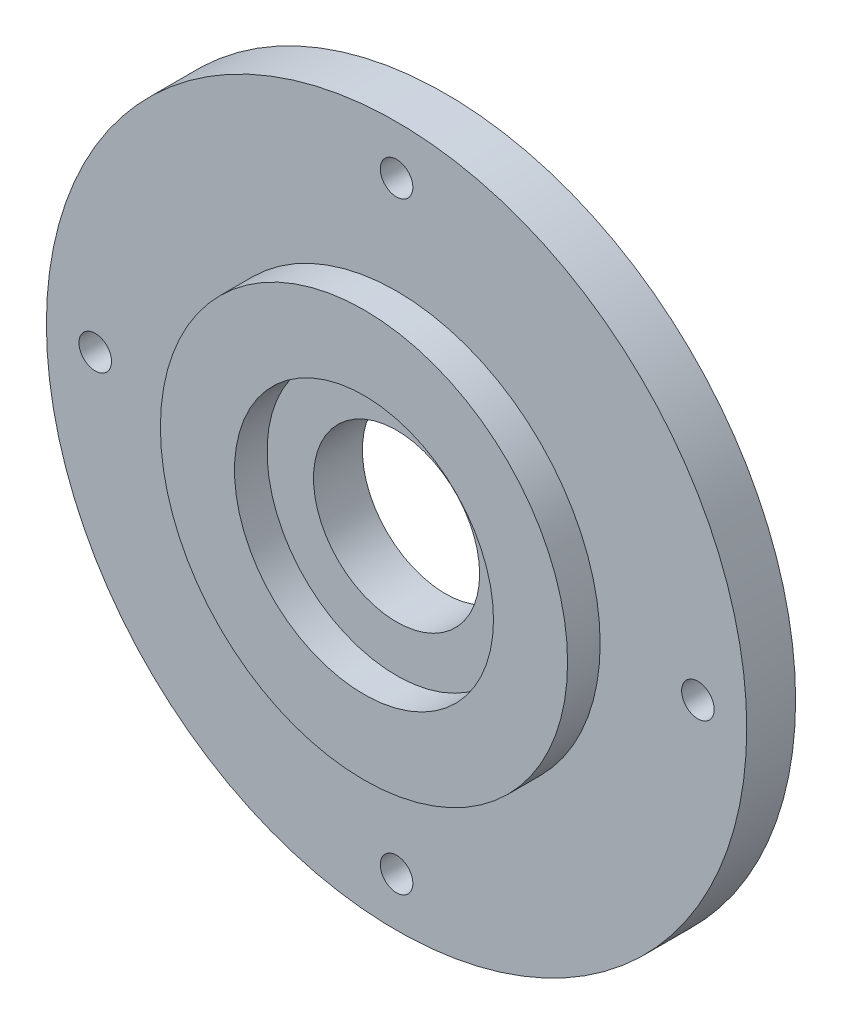
SolidWorks part; units mm, degrees
material "POM 乙缩醛共聚物"
ref_plane "前视基准面" through (0, 0, 0) normal (0, 0, 1) x (1, 0, 0)
ref_plane "上视基准面" through (0, 0, 0) normal (0, 1, 0) x (1, 0, 0)
ref_plane "右视基准面" through (0, 0, 0) normal (1, 0, 0) x (0, 0, -1)
sketch "草图1" plane through (0, 0, 0) normal (0, 0, 1) x (1, 0, 0)
  circle A0 centre (0, 0) radius 41.5
  circle A1 centre (0, -37) radius 2
  circle A2 centre (-37, 0) radius 2
  circle A3 centre (0, 37) radius 2
  circle A4 centre (37, 0) radius 2
  circle A5 centre (0, 0) radius 10.2
  circle A6 centre (0, 0) radius 40 construction
  point P14 (0, 0)
  dimension "D1" = 41.5
  dimension "D2" = 2
  dimension "D5" = 10.2
  dimension "D6" = 40
  dimension "D3" = 37
  dimension "D4" = 4
extrude "凸台-拉伸1" add sketch "草图1" along normal blind 6
sketch "草图3" plane through (0, 0, 6) normal (0, 0, 1) x (1, 0, 0)
  circle A0 centre (0, 0) radius 15.9
  circle A1 centre (0, 0) radius 25
  dimension "D1" = 15.9
  dimension "D2" = 25
sketch "草图4" plane through (0, 0, 0) normal (0, 0, -1) x (-1, 0, 0)
  line L0 (-37, 0) -> (0, -37) construction
  line L5 (19.799, -4.2426) -> (4.2426, -19.799) construction
  line L6 (19.799, -4.2426) -> (-4.2426, 19.799) construction
  line L7 (4.2426, -19.799) -> (-19.799, 4.2426) construction
  line L8 (-4.2426, 19.799) -> (-19.799, 4.2426) construction
  line L9 (19.799, -4.2426) -> (-19.799, 4.2426) construction
  line L10 (4.2426, -19.799) -> (-4.2426, 19.799) construction
  circle A4 centre (-19.799, 4.2426) radius 1.65
  circle A5 centre (-4.2426, 19.799) radius 1.65
  circle A6 centre (19.799, -4.2426) radius 1.65
  circle A7 centre (4.2426, -19.799) radius 1.65
  point P0 (0, 0)
  point P2 (0, 0)
  dimension "D1" = 22
  dimension "D2" = 34
  dimension "D3" = 3.3
  dimension "D4" = 3.3
  dimension "D5" = 3.3
  dimension "D6" = 3.3
extrude "切除-拉伸1" cut sketch "草图4" against normal through all both and the other way through all
extrude "凸台-拉伸2" add sketch "草图3" along normal blind 4
sketch "草图5" plane through (0, 0, 6) normal (0, 0, 1) x (1, 0, 0)
  circle A0 centre (0, 0) radius 41.5
  circle A1 centre (0, 0) radius 43
  dimension "D1" = 86
  dimension "D2" = 83
extrude "凸台-拉伸4" add sketch "草图5" against normal up to surface (6 mm away) up to face at (21.449, 4.2426, 0)
